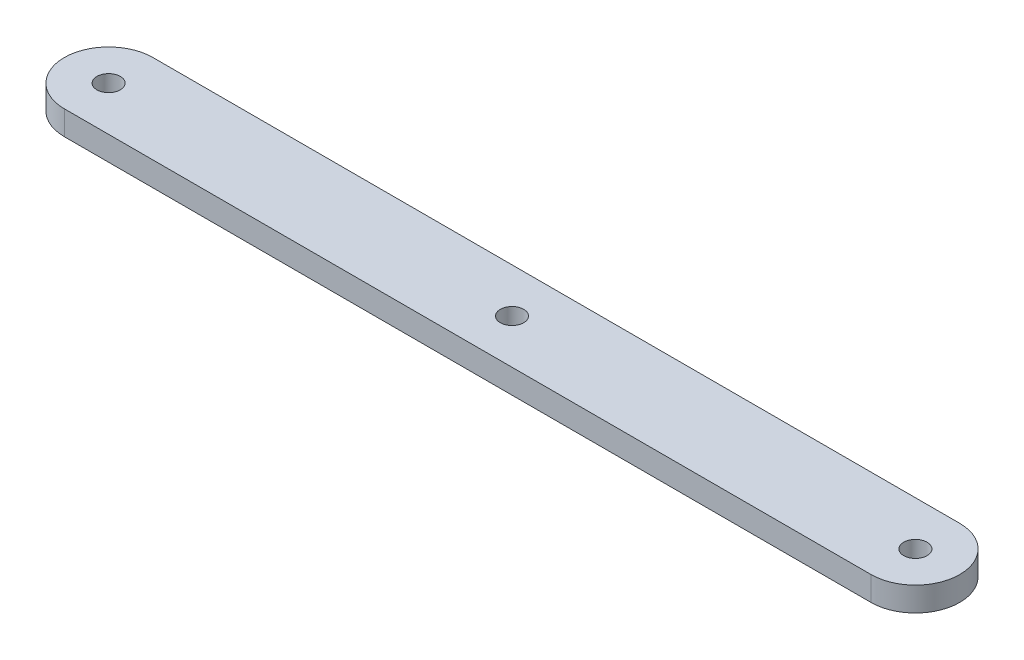
SolidWorks part; units mm, degrees
ref_plane "Front Plane" through (0, 0, 0) normal (0, 0, 1) x (1, 0, 0)
ref_plane "Top Plane" through (0, 0, 0) normal (0, 1, 0) x (1, 0, 0)
ref_plane "Right Plane" through (0, 0, 0) normal (1, 0, 0) x (0, 0, -1)
sketch "Sketch1" plane through (0, 0, 0) normal (0, 1, 0) x (1, 0, 0)
  line L0 (0, 0) -> (145.04, 0) construction
  line L1 (0, 7.9735) -> (145.04, 7.9735)
  line L2 (0, -7.9735) -> (145.04, -7.9735)
  arc A0 (0, 7.9735) -> (0, -7.9735) centre (0, 0) ccw
  arc A1 (145.04, -7.9735) -> (145.04, 7.9735) centre (145.04, 0) ccw
  circle A2 centre (145.04, 0) radius 2.1
  circle A3 centre (72.52, 0) radius 2.1
  circle A4 centre (0, 0) radius 2.1
  point P3 (72.52, 0)
  dimension "D1" = 4.2
  dimension "D2" = 4.2
  dimension "D3" = 4.2
extrude "Boss-Extrude1" add sketch "Sketch1" along normal blind 4.35
